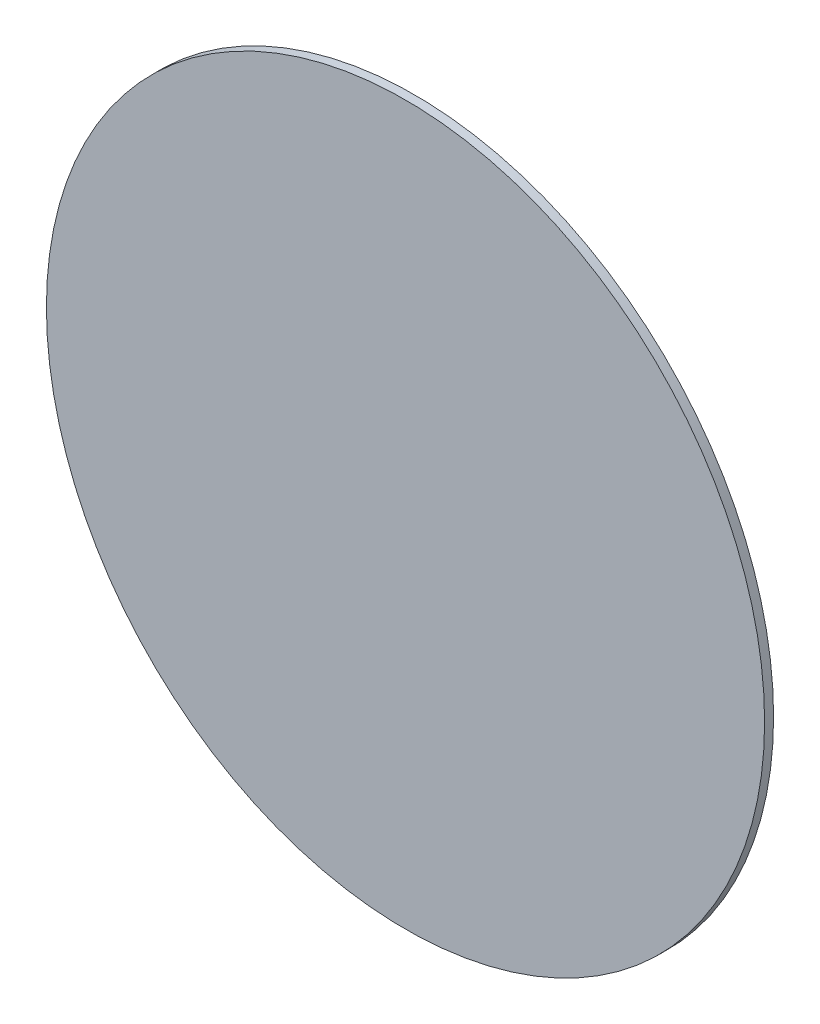
SolidWorks part; units mm, degrees
material "瓦楞纸"
ref_plane "前视基准面" through (0, 0, 0) normal (0, 0, 1) x (1, 0, 0)
ref_plane "上视基准面" through (0, 0, 0) normal (0, 1, 0) x (1, 0, 0)
ref_plane "右视基准面" through (0, 0, 0) normal (1, 0, 0) x (0, 0, -1)
sketch "Sketch1" plane through (0, 0, 0) normal (0, 0, 1) x (1, 0, 0)
  circle A0 centre (0, 0) radius 20
  dimension "D1" = 40
extrude "Extrude1" add sketch "Sketch1" along normal blind 0.5
